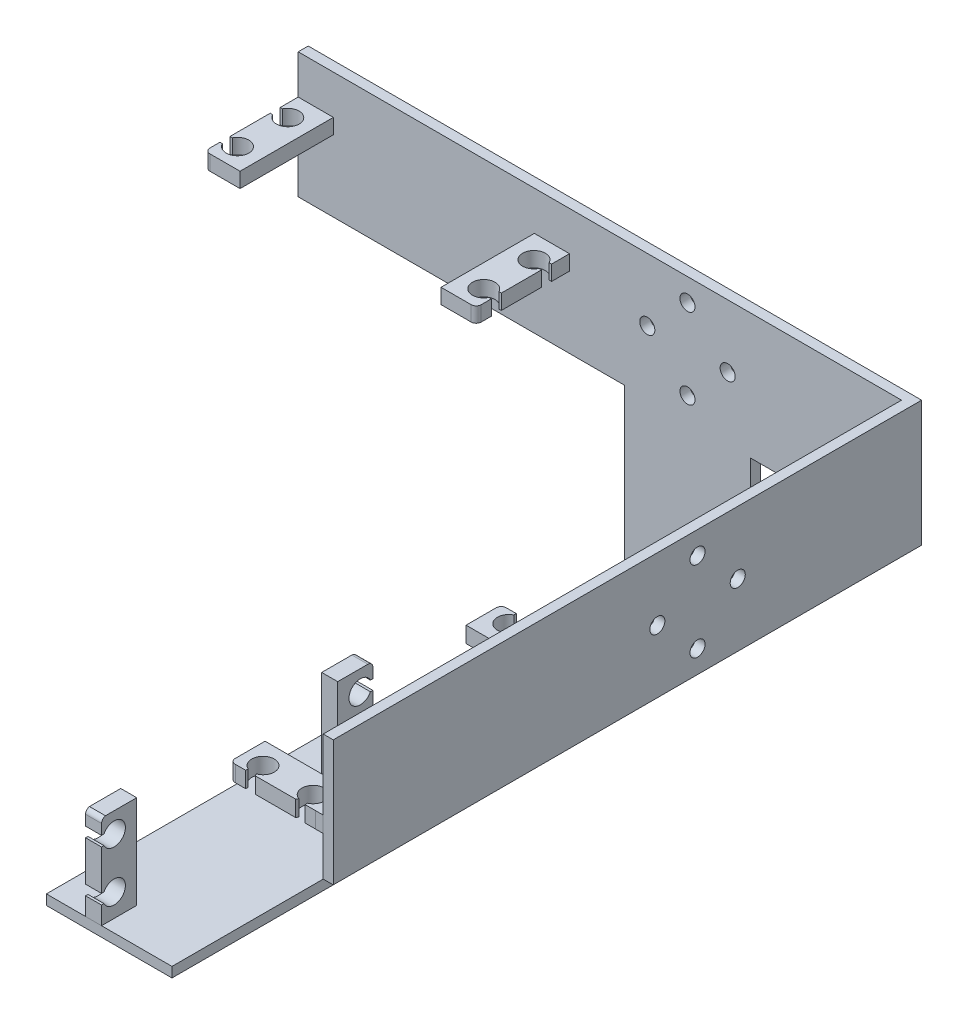
SolidWorks part; units mm, degrees
ref_plane "Front Plane" through (0, 0, 0) normal (0, 0, 1) x (1, 0, 0)
ref_plane "Top Plane" through (0, 0, 0) normal (0, 1, 0) x (1, 0, 0)
ref_plane "Right Plane" through (0, 0, 0) normal (1, 0, 0) x (0, 0, -1)
sketch "Sketch1" plane through (0, 0, 0) normal (0, 1, 0) x (1, 0, 0)
  line L0 (0, 0) -> (102.1, 0)
  line L1 (102.1, -102.1) -> (100.1, -102.1)
  line L2 (100.1, -102.1) -> (100.1, -2)
  line L3 (100.1, -2) -> (0, -2)
  line L4 (0, -2) -> (0, 0)
  line L5 (102.1, 0) -> (102.1, -102.1)
  dimension "D1" = 102.1
  dimension "D3" = 2
  dimension "D4" = 2
extrude "Boss-Extrude1" add sketch "Sketch1" against normal blind 25
sketch "Sketch2" plane through (0, 0, 0) normal (0, 0, -1) x (-1, 0, 0)
  line L0 (-57.5, -4.5) -> (-57.5, -20.5) construction
  line L1 (-65.5, -12.5) -> (-49.5, -12.5) construction
  line L2 (-57.5, -12.5) -> (-57.5, -25) construction
  line L3 (-102.1, -25) -> (-102.1, 0) construction
  line L4 (-102.1, -25) -> (0, -25) construction
  line L5 (-57.5, -12.5) -> (-57.5, 0) construction
  line L6 (-102.1, 0) -> (0, 0) construction
  line L8 (-57.5, -12.5) -> (0, -12.5) construction
  line L9 (0, -25) -> (0, 0) construction
  circle A0 centre (-65.5, -12.5) radius 1.5
  circle A1 centre (-57.5, -20.5) radius 1.5
  circle A2 centre (-49.5, -12.5) radius 1.5
  circle A12 centre (-57.5, -4.5) radius 1.5
  point P6 (-57.5, -12.5)
  dimension "D1" = 57.5
  dimension "D2" = 16
  dimension "D3" = 11.3137
  dimension "D6" = 11.3137
  dimension "D8" = 16
sketch "Sketch3" plane through (102.1, 0, 0) normal (1, 0, 0) x (0, 0, -1)
  line L0 (-44.6, -4.5) -> (-44.6, -20.5) construction
  line L1 (-52.6, -12.5) -> (-36.6, -12.5) construction
  line L2 (-44.6, -12.5) -> (-44.6, -25) construction
  line L4 (-44.6, -12.5) -> (-44.6, 0) construction
  line L5 (-44.6, -12.5) -> (-102.1, -12.5) construction
  line L6 (-102.1, -25) -> (-102.1, 0) construction
  circle A0 centre (-52.6, -12.5) radius 1.5
  circle A1 centre (-44.6, -20.5) radius 1.5
  circle A2 centre (-36.6, -12.5) radius 1.5
  circle A12 centre (-44.6, -4.5) radius 1.5
  point P2 (-44.6, -12.5)
  point P3 (-44.6, -12.5)
  dimension "D8" = 3
  dimension "D9" = 3
  dimension "D2" = 16
  dimension "D6" = 11.3137
  dimension "D7" = 16
  dimension "D10" = 57.5
extrude "Cut-Extrude1" cut sketch "Sketch2" against normal blind 11.3137
extrude "Cut-Extrude2" cut sketch "Sketch3" against normal blind 25 contours A12 | A2 | A0 | A1
ref_plane "Plane1" through (0, -25, 0) normal (0, -1, 0) x (-1, 0, 0)
sketch "Sketch4" plane through (0, -25, 0) normal (0, -1, 0) x (-1, 0, 0)
  line L0 (-100.1, -2) -> (-100.1, -102.1) construction
  line L1 (0, -2) -> (-100.1, -2) construction
  line L2 (-100.1, -2) -> (-100.1, -102.1) construction
  line L3 (0, -2) -> (-100.1, -2) construction
  line L4 (0, -44.6) -> (-57.5, -44.6) construction
  line L5 (-57.5, -102.1) -> (-57.5, -44.6) construction
  line L6 (-57.5, -44.6) -> (-57.5, -2) construction
  line L7 (-57.5, -44.6) -> (-100.1, -44.6) construction
  line L8 (-70, -102.1) -> (-70, -2)
  line L9 (-45, -2) -> (-45, -102.1)
  line L10 (-70, -12.6276) -> (-57.5, -12.6276) construction
  line L11 (-57.5, -12.6276) -> (-45, -12.6276) construction
  line L12 (-70, -102.1) -> (-45, -102.1)
  line L14 (-70, -2) -> (-70, 0)
  line L15 (-102.1, 0) -> (0, 0) construction
  line L16 (-70, 0) -> (-45, 0)
  line L17 (-45, 0) -> (-45, -2)
  dimension "D1" = 57.5
  dimension "D2" = 57.5
  dimension "D3" = 25
extrude "Boss-Extrude2" add sketch "Sketch4" along normal blind 32.1
sketch "Sketch6" plane through (0, 0, 102.1) normal (0, 0, 1) x (1, 0, 0)
  line L0 (45, -25) -> (70, -25)
  line L1 (70, -25) -> (70, -55.1)
  line L2 (70, -57.1) -> (70, -25) construction
  line L3 (70, -55.1) -> (45, -55.1)
  line L4 (45, -57.1) -> (45, -25) construction
  line L5 (45, -55.1) -> (45, -25)
  line L6 (70, -57.1) -> (45, -57.1) construction
  dimension "D1" = 2
extrude "Cut-Extrude3" cut sketch "Sketch6" against normal blind 100.1
sketch "Sketch10" plane through (0, -55.1, 0) normal (0, 1, 0) x (1, 0, 0)
  line L0 (57.5, -36.6) -> (57.5, -52.6) construction
  line L1 (49.5, -44.6) -> (65.5, -44.6) construction
  line L2 (57.5, -44.6) -> (57.5, 22.0778) construction
  line L3 (57.5, -44.6) -> (57.5, 47.0778) construction
  line L4 (57.5, -44.6) -> (57.5, -102.1) construction
  line L5 (45, -2) -> (45, -102.1) construction
  line L7 (70, -102.1) -> (45, -102.1) construction
  circle A0 centre (49.5, -44.6) radius 1.5
  circle A1 centre (57.5, -52.6) radius 1.5
  circle A2 centre (65.5, -44.6) radius 1.5
  circle A3 centre (57.5, -36.6) radius 1.5
  point P1 (57.5, -44.6)
  point P2 (57.5, -44.6)
  point P16 (57.5, -102.1)
  dimension "D4" = 3
  dimension "D5" = 3
  dimension "D1" = 16
  dimension "D2" = 11.3137
  dimension "D3" = 16
  dimension "D6" = 57.5
extrude "Cut-Extrude4" cut sketch "Sketch10" against normal blind 3
sketch "Sketch11" plane through (102.1, 0, 0) normal (1, 0, 0) x (0, 0, -1)
  line L0 (-102.1, 0) -> (-102.1, -25)
  line L1 (-102.1, -25) -> (-117.1, -25)
  line L2 (-55.055, -25) -> (55.055, -25) construction
  line L3 (-117.1, -25) -> (-117.1, 0)
  line L4 (-117.1, 0) -> (-102.1, 0)
  dimension "D1" = 15
extrude "Boss-Extrude3" add sketch "Sketch11" against normal blind 2
sketch "Sketch12" plane through (0, -55.1, 0) normal (0, 1, 0) x (1, 0, 0)
  line L0 (45, -102.1) -> (70, -102.1)
  line L1 (70, -102.1) -> (70, -117.1)
  line L2 (70, -117.1) -> (45, -117.1)
  line L4 (45, -117.1) -> (45, -102.1)
  dimension "D1" = 15
extrude "Boss-Extrude4" add sketch "Sketch12" against normal blind 2
sketch "Sketch14" plane through (0, 0, 0) normal (0, 0, -1) x (-1, 0, 0)
  line L0 (0, 0) -> (0, -25)
  line L1 (0, -25) -> (19.9824, -25)
  line L2 (19.9824, -25) -> (19.9824, 0)
  line L3 (19.9824, 0) -> (0, 0)
extrude "Boss-Extrude5" add sketch "Sketch14" against normal blind 2
sketch "Sketch16" plane through (0, -25, 0) normal (0, -1, 0) x (-1, 0, 0)
  line L0 (-99.5, -110.1) -> (-99.5, -116.0992)
  line L1 (-98.4613, -117.0434) -> (-96.4616, -117.0434)
  line L2 (-96.4616, -117.0434) -> (-96.4507, -116.5591)
  line L3 (-94.7867, -116.6393) -> (-94.5196, -117.0434)
  line L4 (-94.5196, -117.0434) -> (-86.5207, -117.0434)
  line L5 (-86.5207, -117.0434) -> (-86.3074, -116.6085)
  line L6 (-84.6103, -116.5591) -> (-84.6183, -117.0434)
  line L7 (-84.6183, -117.0434) -> (-82.6186, -117.0434)
  line L8 (-81.5268, -116.0992) -> (-81.5268, -110.1)
  line L9 (-81.5268, -110.1) -> (-99.5, -110.1)
  line L10 (-99.5, -110.1) -> (-100.1, -110.1) construction
  line L12 (-100.1, -2) -> (-100.1, -117.1) construction
  line L13 (-99.5, -116.0992) -> (-100.1, -116.0992) construction
  arc A0 (-99.5, -116.0992) -> (-98.4613, -117.0434) centre (-98.5015, -116.0442) ccw
  arc A1 (-94.7867, -116.6393) -> (-96.4507, -116.5591) centre (-95.5181, -114.5115) ccw
  arc A2 (-84.6103, -116.5591) -> (-86.3074, -116.6085) centre (-85.5195, -114.5009) ccw
  arc A3 (-82.6186, -117.0434) -> (-81.5268, -116.0992) centre (-82.5255, -116.0478) ccw
  point P21 (-81.8713, -116.8042)
  dimension "D10" = 2.25
  dimension "D11" = 2.25
  dimension "D13" = 9.9986
  dimension "D14" = 1
  dimension "D15" = 1
  dimension "D12" = 3.3541
  dimension "D2" = 5.9992
  dimension "D3" = 1.9997
  dimension "D4" = 7.9989
  dimension "D5" = 1.9997
  dimension "D6" = 5.9992
  dimension "D7" = 0.6
  dimension "D8" = 90
  dimension "D9" = 90
  dimension "D16" = 0.4844
  dimension "D17" = 0.4844
  dimension "D18" = 0.4844
  dimension "D19" = 0.4844
  dimension "D20" = 4.3144
  dimension "D21" = 17.9732
  dimension "D22" = 6.9434
  dimension "D23" = 6.9434
  dimension "D24" = 6.9434
  dimension "D25" = 8
extrude "Boss-Extrude6" add sketch "Sketch16" against normal blind 10.98 separate body contours L0 A0 L1 L2 A1 L3 L4 L5 A2 L6 L7 A3 L8 L9
sketch "Sketch18" plane through (0, -25, 0) normal (0, -1, 0) x (1, 0, 0)
  line L10 (81.5268, 110.1) -> (99.5, 110.1)
  line L11 (99.5, 110.1) -> (99.5, 116.0992)
  line L12 (98.4613, 117.0434) -> (96.4616, 117.0434)
  line L13 (96.4616, 117.0434) -> (96.4507, 116.5591)
  line L14 (94.7867, 116.6393) -> (94.5196, 117.0434)
  line L15 (94.5196, 117.0434) -> (86.5207, 117.0434)
  line L16 (86.5207, 117.0434) -> (86.3074, 116.6085)
  line L17 (84.6103, 116.5591) -> (84.6183, 117.0434)
  line L18 (84.6183, 117.0434) -> (82.6186, 117.0434)
  line L19 (81.5268, 116.0992) -> (81.5268, 110.1)
  line L20 (81.5268, 110.1) -> (99.5, 110.1)
  line L21 (99.5, 110.1) -> (99.5, 116.0992)
  line L22 (98.4613, 117.0434) -> (96.4616, 117.0434)
  line L23 (96.4616, 117.0434) -> (96.4507, 116.5591)
  line L24 (94.7867, 116.6393) -> (94.5196, 117.0434)
  line L25 (94.5196, 117.0434) -> (86.5207, 117.0434)
  line L26 (86.5207, 117.0434) -> (86.3074, 116.6085)
  line L27 (84.6103, 116.5591) -> (84.6183, 117.0434)
  line L28 (84.6183, 117.0434) -> (82.6186, 117.0434)
  line L29 (81.5268, 116.0992) -> (81.5268, 110.1)
  arc A4 (99.5, 116.0992) -> (98.4613, 117.0434) centre (98.5015, 116.0442) ccw
  arc A5 (94.7867, 116.6393) -> (96.4507, 116.5591) centre (95.5181, 114.5115) ccw
  arc A6 (84.6103, 116.5591) -> (86.3074, 116.6085) centre (85.5195, 114.5009) ccw
  arc A7 (82.6186, 117.0434) -> (81.5268, 116.0992) centre (82.5255, 116.0478) ccw
  arc A8 (99.5, 116.0992) -> (98.4613, 117.0434) centre (98.5015, 116.0442) ccw
  arc A9 (94.7867, 116.6393) -> (96.4507, 116.5591) centre (95.5181, 114.5115) ccw
  arc A10 (84.6103, 116.5591) -> (86.3074, 116.6085) centre (85.5195, 114.5009) ccw
  arc A11 (82.6186, 117.0434) -> (81.5268, 116.0992) centre (82.5255, 116.0478) ccw
  dimension "D1" = 0
extrude "Cut-Extrude5" cut sketch "Sketch18" against normal blind 7.8
sketch "Sketch19" plane through (0, -14.02, 0) normal (0, 1, 0) x (1, 0, 0)
  line L1 (100.1, -117.0434) -> (100.1, -110.1)
  line L2 (100.1, -2) -> (100.1, -117.1) construction
  line L5 (100.1, -117.0434) -> (98.4613, -117.0434)
  line L7 (98.4613, -117.0434) -> (98.4613, -110.1)
  line L12 (81.5268, -110.1) -> (99.5, -110.1) construction
  line L13 (98.4613, -110.1) -> (100.1, -110.1)
extrude "Boss-Extrude7" add sketch "Sketch19" against normal up to vertex (3.18 mm away)
sketch "Sketch20" plane through (0, -25, 0) normal (0, -1, 0) x (-1, 0, 0)
  line L20 (-81.5268, -70.1) -> (-81.5268, -64.1)
  line L21 (-82.5268, -63.1) -> (-84.5268, -63.1)
  line L22 (-84.5268, -63.1) -> (-84.5268, -63.5844)
  line L23 (-86.5268, -63.5844) -> (-86.5268, -63.1)
  line L24 (-86.5268, -63.1) -> (-94.5268, -63.1)
  line L25 (-94.5268, -63.1) -> (-94.5268, -63.5844)
  line L26 (-96.5268, -63.5844) -> (-96.5268, -63.1)
  line L29 (-100.1, -70.1) -> (-81.5268, -70.1)
  line L30 (-100.1, -110.1) -> (-81.5268, -110.1) construction
  line L31 (-81.5268, -116.0992) -> (-81.5268, -110.1) construction
  line L32 (-100.1, -102.1) -> (-100.1, -2) construction
  line L33 (-100.1, -110.1) -> (-81.5268, -110.1) construction
  line L34 (-96.5268, -63.1) -> (-100.1, -63.1)
  line L35 (-100.1, -63.1) -> (-100.1, -70.1)
  arc A8 (-81.5268, -64.1) -> (-82.5268, -63.1) centre (-82.5268, -64.1) ccw
  arc A9 (-86.5268, -63.5844) -> (-84.5268, -63.5844) centre (-85.5268, -65.6) ccw
  arc A10 (-96.5268, -63.5844) -> (-94.5268, -63.5844) centre (-95.5268, -65.6) ccw
  dimension "D5" = 1
  dimension "D6" = 2.25
  dimension "D1" = 3.3541
  dimension "D2" = 18.5732
  dimension "D3" = 7
  dimension "D4" = 4.5
  dimension "D7" = 40
extrude "Boss-Extrude8" add sketch "Sketch20" against normal blind 10.98
sketch "Sketch22" plane through (0, -25, 0) normal (0, -1, 0) x (1, 0, 0)
  line L0 (100.1, 70.1) -> (100.1, 63.1)
  line L1 (100.1, 63.1) -> (81.0738, 63.1)
  line L2 (81.0738, 63.1) -> (81.0738, 70.1)
  line L3 (81.0738, 70.1) -> (100.1, 70.1)
extrude "Cut-Extrude6" cut sketch "Sketch22" against normal blind 7.8
ref_plane "Plane2" through (45, 0, 0) normal (-1, 0, 0) x (0, 0, 1)
sketch "Sketch25" plane through (45, 0, 0) normal (-1, 0, 0) x (0, 0, 1)
  line L0 (117.1, -55.1) -> (117.1, -36.53)
  line L1 (117.1, -36.53) -> (110.1, -36.53)
  line L2 (110.1, -36.53) -> (110.1, -55.1)
  line L3 (2, -55.1) -> (117.1, -55.1) construction
  line L4 (110.1, -55.1) -> (117.1, -55.1)
  line L5 (70.1, -55.1) -> (70.1, -36.53)
  line L6 (70.1, -36.53) -> (63.1, -36.53)
  line L7 (63.1, -36.53) -> (63.1, -55.1)
  line L8 (63.1, -55.1) -> (70.1, -55.1)
  point P9 (0, 0)
  point P12 (0, 0)
  dimension "D1" = 18.57
  dimension "D2" = 40
  dimension "D3" = 7
  dimension "D4" = 7
extrude "Boss-Extrude9" add sketch "Sketch25" against normal blind 10.98 separate body
sketch "Sketch27" plane through (45, 0, 0) normal (-1, 0, 0) x (0, 0, 1)
  line L1 (117.1, -55.1) -> (117.1, -51.53)
  line L2 (117.1, -51.53) -> (116.6156, -51.53)
  line L3 (116.6156, -49.53) -> (117.1, -49.53)
  line L4 (117.1, -49.53) -> (117.1, -41.53)
  line L5 (117.1, -41.53) -> (116.6156, -41.53)
  line L6 (116.6156, -39.53) -> (117.1, -39.53)
  line L7 (117.1, -39.53) -> (117.1, -37.53)
  line L8 (116.3252, -36.53) -> (110.1, -36.53)
  line L9 (110.1, -36.53) -> (110.1, -55.1)
  line L10 (63.1, -36.53) -> (63.1, -55.1) construction
  line L11 (117.1, -36.53) -> (117.1, -37.53)
  line L12 (117.1, -39.53) -> (117.1, -41.53)
  line L13 (117.1, -36.53) -> (110.1, -36.53) construction
  line L14 (117.1, -55.1) -> (117.1, -36.53) construction
  line L15 (110.1, -55.1) -> (117.1, -55.1)
  line L16 (116.3252, -36.53) -> (117.1, -36.53)
  line L17 (117.1, -36.53) -> (117.1, -37.53)
  line L18 (117.1, -49.53) -> (117.1, -51.53)
  arc A1 (116.6156, -49.53) -> (116.6156, -51.53) centre (114.6, -50.53) ccw
  arc A2 (116.6156, -39.53) -> (116.6156, -41.53) centre (114.6, -40.53) ccw
  arc A3 (117.1, -37.53) -> (116.3252, -36.53) centre (116.1003, -37.5044) ccw
  point P1 (0, 0)
  point P22 (0, 0)
extrude "Cut-Extrude9" cut sketch "Sketch27" against normal blind 10.98 contours L6 A2 L5 L12 | L3 A1 L2 L18 | A3 L11 L16
sketch "Sketch28" plane through (45, 0, 0) normal (-1, 0, 0) x (0, 0, 1)
  line L0 (110.1, -36.53) -> (117.126, -36.53)
  line L1 (117.126, -36.53) -> (117.1, -55.1)
  line L2 (117.1, -55.1) -> (110.1, -55.1)
  line L3 (110.1, -55.1) -> (110.1, -36.53)
extrude "Cut-Extrude10" cut sketch "Sketch28" against normal blind 7.8
sketch "Sketch29" plane through (45, 0, 0) normal (-1, 0, 0) x (0, 0, 1)
  line L0 (70.1, -36.53) -> (64.1, -36.53)
  line L1 (63.1, -37.53) -> (63.1, -39.53)
  line L2 (63.1, -39.53) -> (63.5844, -39.53)
  line L3 (63.5844, -41.53) -> (63.1, -41.53)
  line L4 (63.1, -41.53) -> (63.1, -49.53)
  line L5 (63.1, -49.53) -> (63.5844, -49.53)
  line L6 (63.5844, -51.53) -> (63.1, -51.53)
  line L7 (63.1, -51.53) -> (63.1, -55.1)
  line L9 (70.1, -55.1) -> (70.1, -36.53)
  line L11 (70.1, -55.1) -> (70.1, -36.53) construction
  line L12 (70.1, -36.53) -> (63.1, -36.53) construction
  line L13 (2, -55.1) -> (117.1, -55.1) construction
  line L14 (63.1, -36.53) -> (63.1, -55.1) construction
  line L15 (64.1, -36.53) -> (63.1, -36.53)
  line L16 (63.1, -36.53) -> (63.1, -37.53)
  line L17 (63.1, -39.53) -> (63.1, -41.53)
  line L18 (63.1, -49.53) -> (63.1, -51.53)
  line L19 (63.1, -55.1) -> (70.1, -55.1)
  arc A0 (64.1, -36.53) -> (63.1, -37.53) centre (64.1, -37.53) ccw
  arc A1 (63.5844, -41.53) -> (63.5844, -39.53) centre (65.6, -40.53) ccw
  arc A2 (63.5844, -51.53) -> (63.5844, -49.53) centre (65.6, -50.53) ccw
  point P9 (0, 0)
  line M17 (70.1, -36.53) -> (63.1, -36.53)
  line M18 (63.1, -36.53) -> (63.1, -55.1)
extrude "Cut-Extrude11" cut sketch "Sketch29" against normal through all contours L3 A1 L2 M18 | L6 A2 L5 M18 | A0 M17 M18
sketch "Sketch30" plane through (45, 0, 0) normal (-1, 0, 0) x (0, 0, 1)
  line L0 (70.1, -36.53) -> (70.1, -55.1)
  line L1 (70.1, -55.1) -> (63.1, -55.1)
  line L2 (63.1, -55.1) -> (63.1, -36.53)
  line L3 (63.1, -36.53) -> (70.1, -36.53)
  point P7 (0, 0)
  point P8 (63.1, -37.53)
  point P9 (63.1, -36.53)
  point P12 (63.1, -37.53)
  point P13 (63.1, -37.53)
  point P14 (63.1, -37.53)
extrude "Cut-Extrude12" cut sketch "Sketch30" against normal blind 7.8
ref_plane "Plane7" through (0, 0, 0) normal (0, 1, 0) x (1, 0, 0)
sketch "Sketch31" plane through (0, 0, 0) normal (0, 1, 0) x (1, 0, 0)
  line L5 (34.0176, -20.57) -> (34.0176, -2)
  line L6 (34.0176, -2) -> (27.0176, -2)
  line L7 (27.0176, -2) -> (27.0176, -20.57)
  line L8 (27.0176, -20.57) -> (34.0176, -20.57)
  line L9 (-12.9824, -20.57) -> (-12.9824, -2)
  line L10 (-12.9824, -2) -> (-19.9824, -2)
  line L11 (-19.9824, -2) -> (-19.9824, -20.57)
  line L12 (-19.9824, -20.57) -> (-12.9824, -20.57)
  line L13 (-19.9824, -2) -> (100.1, -2) construction
  line L14 (100.1, -2) -> (0, -2) construction
  point P0 (0, 0)
  dimension "D1" = 18.57
  dimension "D2" = 40
  dimension "D3" = 7
  dimension "D4" = 7
  dimension "D5" = 18.57
extrude "Boss-Extrude10" add sketch "Sketch31" against normal blind 10.8
sketch "Sketch32" plane through (0, 0, 0) normal (0, 1, 0) x (1, 0, 0)
  line L10 (27.0176, -20.57) -> (33.0176, -20.57)
  line L12 (34.0176, -19.57) -> (34.0176, -17.57)
  line L13 (34.0176, -17.57) -> (33.5332, -17.57)
  line L29 (33.5332, -15.57) -> (34.0176, -15.57)
  line L36 (34.0176, -15.57) -> (34.0176, -7.57)
  line L37 (34.0176, -7.57) -> (33.5332, -7.57)
  line L38 (33.5332, -5.57) -> (34.0176, -5.57)
  line L40 (33.0474, -52.0041) -> (27.0176, -52.0041)
  line L43 (27.0176, -20.57) -> (34.0176, -20.57) construction
  line L44 (27.0176, -20.57) -> (27.0176, -2)
  line L45 (27.0176, -2) -> (34.0176, -2)
  line L46 (34.0176, -2) -> (34.0176, -5.57)
  line L47 (33.0176, -20.57) -> (34.0176, -20.57)
  line L48 (34.0176, -20.57) -> (34.0176, -19.57)
  line L49 (34.0176, -17.57) -> (34.0176, -15.57)
  line L50 (34.0176, -7.57) -> (34.0176, -5.57)
  arc A12 (33.0176, -20.57) -> (34.0176, -19.57) centre (33.0176, -19.57) ccw
  arc A13 (33.5332, -15.57) -> (33.5332, -17.57) centre (31.5176, -16.57) ccw
  arc A14 (33.5332, -5.57) -> (33.5332, -7.57) centre (31.5176, -6.57) ccw
  arc A15 (34.0176, -53.6865) -> (33.0474, -52.0041) centre (33.3256, -52.9647) ccw
  line M20 (27.0176, -20.57) -> (34.0176, -20.57)
  line M21 (34.0176, -20.57) -> (34.0176, -2)
extrude "Cut-Extrude13" cut sketch "Sketch32" against normal through all contours L29 A13 L13 M21 | L38 A14 L37 M21 | A12 M20 M21
sketch "Sketch33" plane through (0, 0, 0) normal (0, 1, 0) x (1, 0, 0)
  line L0 (27.0176, -2) -> (34.0176, -2)
  line L1 (34.0176, -2) -> (34.0176, -20.57)
  line L2 (34.0176, -20.57) -> (27.0176, -20.57)
  line L3 (27.0176, -20.57) -> (27.0176, -2)
  line L4 (-12.9824, -2) -> (-19.9824, -2)
  line L5 (-19.9824, -2) -> (-19.9824, -20.57)
  line L6 (-19.9824, -20.57) -> (-12.9824, -20.57)
  line L7 (-12.9824, -20.57) -> (-12.9824, -2)
extrude "Cut-Extrude14" cut sketch "Sketch33" against normal blind 7.8 contours L7 L4 L5 L6 | L3 L0 L1 L2
sketch "Sketch34" plane through (0, -7.8, 0) normal (0, 1, 0) x (1, 0, 0)
  line L1 (-19.9824, -2) -> (-19.9824, -5.57)
  line L2 (-19.9824, -5.57) -> (-19.4979, -5.57)
  line L3 (-19.4979, -7.57) -> (-19.9824, -7.57)
  line L4 (-19.9824, -7.57) -> (-19.9824, -15.57)
  line L5 (-19.9824, -15.57) -> (-19.4979, -15.57)
  line L6 (-19.4979, -17.57) -> (-19.9824, -17.57)
  line L7 (-19.9824, -17.57) -> (-19.9824, -19.57)
  line L8 (-18.9824, -20.57) -> (-12.9824, -20.57)
  line L9 (-12.9824, -20.57) -> (-12.9824, -2)
  line L10 (-12.9824, -20.57) -> (-12.9824, -2) construction
  line L13 (-19.9824, -20.57) -> (-12.9824, -20.57) construction
  line L14 (-19.9824, -2) -> (-12.9824, -2)
  line L15 (-19.9824, -15.57) -> (-19.9824, -17.57)
  line L16 (-19.9824, -19.57) -> (-19.9824, -20.57)
  line L17 (-19.9824, -20.57) -> (-18.9824, -20.57)
  line L18 (-19.9824, -5.57) -> (-19.9824, -7.57)
  arc A1 (-19.4979, -7.57) -> (-19.4979, -5.57) centre (-17.4824, -6.57) ccw
  arc A2 (-19.4979, -17.57) -> (-19.4979, -15.57) centre (-17.4824, -16.57) ccw
  arc A3 (-19.9824, -19.57) -> (-18.9824, -20.57) centre (-18.9824, -19.57) ccw
  line M15 (-19.9824, -20.57) -> (-12.9824, -20.57)
  line M18 (-19.9824, -2) -> (-19.9824, -20.57)
extrude "Cut-Extrude15" cut sketch "Sketch34" against normal blind 11.02 contours L3 A1 L2 M18 | L6 A2 L5 M18 | A3 M18 M15
